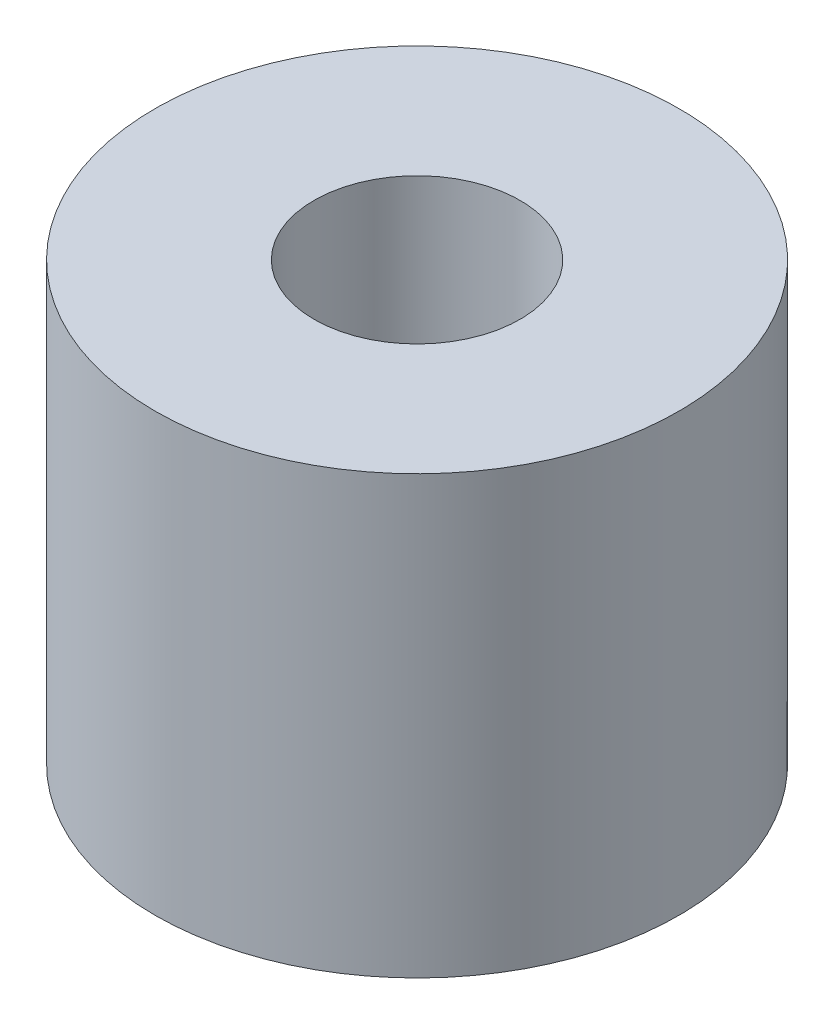
SolidWorks part; units mm, degrees
material "6063-T6"
ref_plane "Front Plane" through (0, 0, 0) normal (0, 0, 1) x (1, 0, 0)
ref_plane "Top Plane" through (0, 0, 0) normal (0, 1, 0) x (1, 0, 0)
ref_plane "Right Plane" through (0, 0, 0) normal (1, 0, 0) x (0, 0, -1)
sketch "Sketch1" plane through (0, 0, 0) normal (0, 1, 0) x (1, 0, 0)
  circle A0 centre (0, 0) radius 15
  circle A1 centre (0, 0) radius 2.5
  point P5 (0, 0)
  dimension "D1" = 30
  dimension "D2" = 5
extrude "Boss-Extrude1" add sketch "Sketch1" along normal blind 25
hole_wizard "G1/4 Tapped Hole1" positions "Sketch2" profile "Sketch4" tap size "G1/4" standard "ISO"
sketch "Sketch2" plane through (0, 25, 0) normal (0, 1, 0) x (1, 0, 0)
  point P0 (0, 0)
sketch "Sketch4" plane through (0, 25, 0) normal (1, 0, 0) x (0, 0, 1)
  line L0 (0, 0) -> (0, 18.5451)
  line L1 (0, 18.5451) -> (5.9, 15)
  line L2 (5.9, 15) -> (5.9, 0)
  line L5 (5.9, 0) -> (0, 0)
  line L10 (0, 18.5451) -> (-5.9, 15) construction
  line L11 (0, -6.35) -> (0, 107.95) construction
  dimension "Tap Drill Dia." = 11.8
  dimension "Tap Drill Depth" = 15
  dimension "Drill Angle" = 118
cosmetic thread "Hole Thread1" parameters "D1"=25, "D2"=13.157
